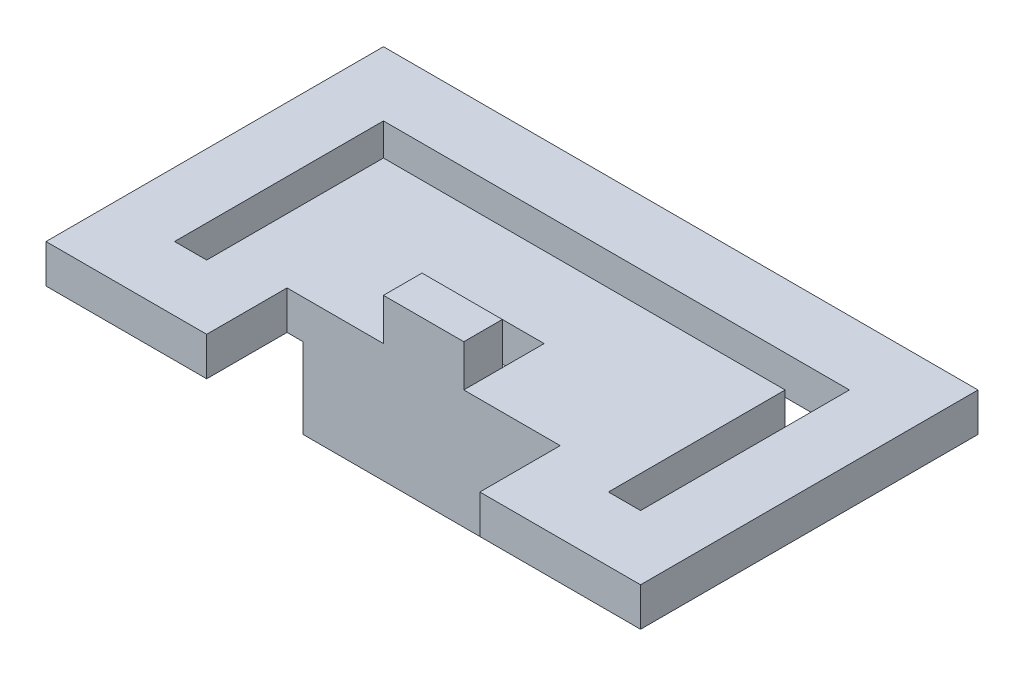
SolidWorks part; units mm, degrees
material "PBT General Purpose"
ref_plane "Front Plane" through (0, 0, 0) normal (0, 0, 1) x (1, 0, 0)
ref_plane "Top Plane" through (0, 0, 0) normal (0, 1, 0) x (1, 0, 0)
ref_plane "Right Plane" through (0, 0, 0) normal (1, 0, 0) x (0, 0, -1)
sketch "Sketch2" plane through (0, 0, 0) normal (0, 0, 1) x (1, 0, 0)
  line L0 (0, 0) -> (0, 0.5)
  line L1 (0, 0.5) -> (0.5, 0.5)
  line L2 (0.5, 0.5) -> (0.5, 1)
  line L3 (0.5, 1) -> (1, 1)
  line L4 (1, 1) -> (1, 0.5)
  line L5 (1, 0.5) -> (1.5, 0.5)
  line L6 (1.5, 0.5) -> (1.5, 0)
  line L7 (1.5, 0) -> (0, 0)
  dimension "D1" = 1.5
  dimension "D2" = 0.5
  dimension "D3" = 0.5
  dimension "D4" = 0.5
  dimension "D5" = 0.5
  dimension "D6" = 0.5
extrude "Boss-Extrude1" add sketch "Sketch2" along normal blind 0.24
sketch "Sketch3" plane through (0, 0.5, 0) normal (0, 1, 0) x (1, 0, 0)
  line L0 (0.5, -0.24) -> (0.5, 0.26)
  line L1 (0.5, 0.26) -> (1, 0.26)
  line L2 (1, 0.26) -> (1, -0.24)
  line L3 (1, -0.24) -> (2, -0.24)
  line L4 (2, -0.24) -> (2, 0.76)
  line L5 (2, 0.76) -> (-0.5, 0.76)
  line L6 (-0.5, 0.76) -> (-0.5, -0.24)
  line L7 (-0.5, -0.24) -> (0.5, -0.24)
  dimension "D1" = 0.5
  dimension "D2" = 1
  dimension "D3" = 1
  dimension "D4" = 1
extrude "Boss-Extrude2" add sketch "Sketch3" along normal blind 0.24
sketch "Sketch4" plane through (0, 0.74, 0) normal (0, 1, 0) x (1, 0, 0)
  line L0 (-0.1, -0.24) -> (-0.1, -0.74)
  line L1 (-0.5, -0.24) -> (0.5, -0.24) construction
  line L2 (-0.1, -0.74) -> (-1.1, -0.74)
  line L3 (-1.1, -0.74) -> (-1.1, 1.36)
  line L4 (-1.1, 1.36) -> (2.6, 1.36)
  line L5 (2.6, 1.36) -> (2.6, -0.74)
  line L6 (2.6, -0.74) -> (1.6, -0.74)
  line L7 (1.6, -0.74) -> (1.6, -0.24)
  line L8 (1, -0.24) -> (2, -0.24) construction
  line L9 (1.6, -0.24) -> (2, -0.24)
  line L10 (2, -0.24) -> (2, -0.34)
  line L11 (2, -0.34) -> (2.2, -0.34)
  line L12 (2.2, -0.34) -> (2.2, 0.96)
  line L13 (2.2, 0.96) -> (-0.7, 0.96)
  line L14 (-0.7, 0.96) -> (-0.7, -0.34)
  line L15 (-0.7, -0.34) -> (-0.5, -0.34)
  line L16 (-0.5, -0.34) -> (-0.5, -0.24)
  line L17 (2, 0.76) -> (-0.5, 0.76) construction
  line L18 (2, -0.24) -> (2, 0.76) construction
  line L19 (-0.1, -0.24) -> (-0.5, -0.24)
  dimension "D1" = 0.4
  dimension "D2" = 0.4
  dimension "D3" = 0.1
  dimension "D4" = 0.2
  dimension "D5" = 0.2
  dimension "D6" = 0.2
  dimension "D7" = 0.1
  dimension "D8" = 0.5
  dimension "D9" = 0.5
  dimension "D10" = 1
  dimension "D11" = 1
  dimension "D12" = 0.4
extrude "Boss-Extrude3" add sketch "Sketch4" against normal blind 0.24
